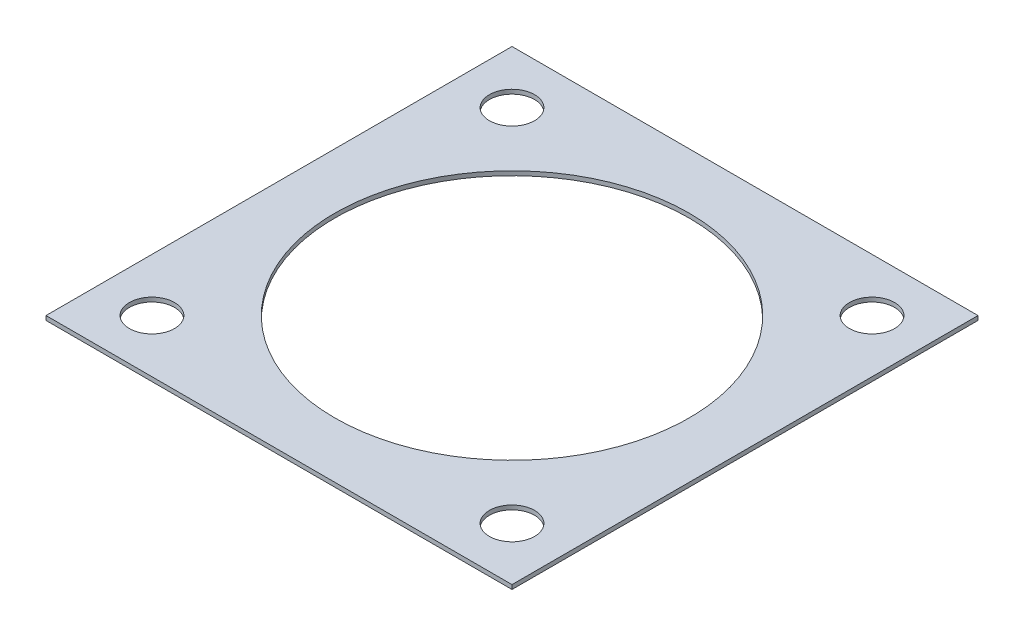
SolidWorks part; units mm, degrees
ref_plane "Front Plane" through (0, 0, 0) normal (0, 0, 1) x (1, 0, 0)
ref_plane "Top Plane" through (0, 0, 0) normal (0, 1, 0) x (1, 0, 0)
ref_plane "Right Plane" through (0, 0, 0) normal (1, 0, 0) x (0, 0, -1)
sketch "Sketch1" plane through (0, 0, 0) normal (0, 1, 0) x (1, 0, 0)
  line L1 (-54.5113, 54.5113) -> (54.5113, 54.5113)
  line L2 (-54.5113, 54.5113) -> (-54.5113, -54.5113)
  line L3 (-54.5113, -54.5113) -> (54.5113, -54.5113)
  line L4 (54.5113, 54.5113) -> (54.5113, -54.5113)
  line L5 (-54.5113, 54.5113) -> (54.5113, -54.5113) construction
  line L6 (-54.5113, -54.5113) -> (54.5113, 54.5113) construction
  circle A0 centre (0, 0) radius 41.4776
  circle A1 centre (42.1163, 42.1163) radius 5.281
  circle A2 centre (42.1163, -42.1163) radius 5.281
  circle A3 centre (-42.1163, -42.1163) radius 5.281
  circle A4 centre (-42.1163, 42.1163) radius 5.281
  point P18 (0, 0)
  dimension "D1" = 4
extrude "Boss-Extrude1" add sketch "Sketch1" along normal blind 1
